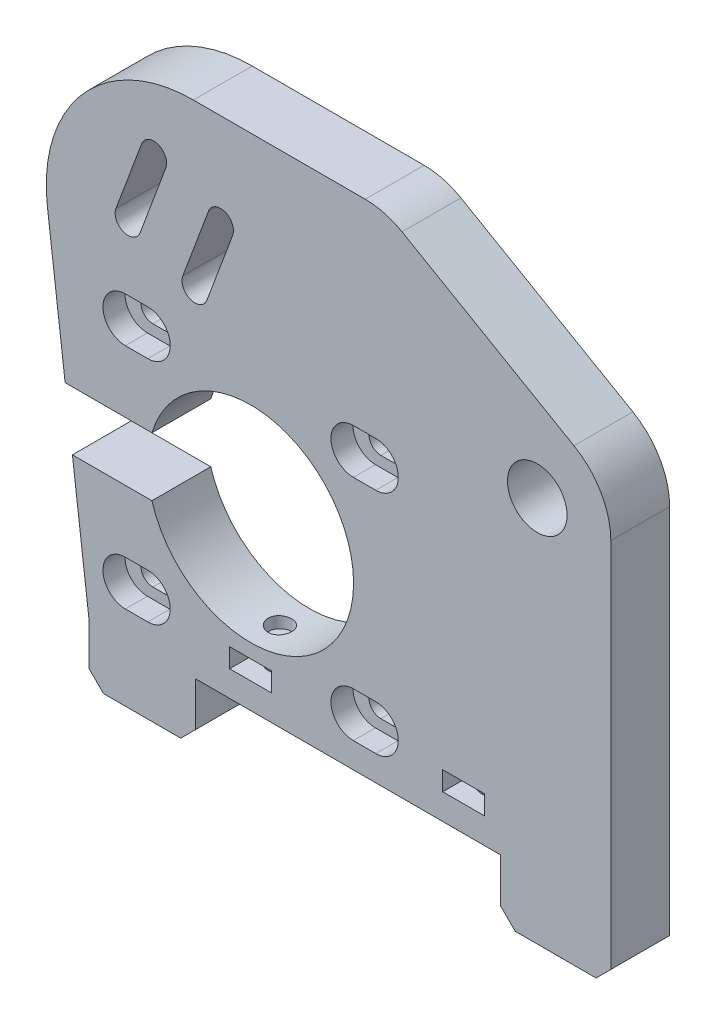
SolidWorks part; units mm, degrees
ref_plane "前视基准面" through (0, 0, 0) normal (0, 0, 1) x (1, 0, 0)
ref_plane "上视基准面" through (0, 0, 0) normal (0, 1, 0) x (1, 0, 0)
ref_plane "右视基准面" through (0, 0, 0) normal (1, 0, 0) x (0, 0, -1)
sketch "草图1" plane through (0, 0, 0) normal (0, 0, 1) x (1, 0, 0)
  line B0 (-25.2132, 4) -> (-29.6202, 39.6595)
  line B1 (-13.4164, 4) -> (-25.2132, 4)
  line B2 (-24.2245, -4) -> (-13.4164, -4)
  line B3 (-22, -22) -> (-24.2245, -4)
  line B4 (-7.5, -30) -> (-22, -30)
  line B5 (-7.5, -30) -> (-7.5, -22)
  line B6 (33.9711, -22) -> (-7.5, -22)
  line B7 (-14.7, 13.9) -> (-16.3, 13.9)
  line B8 (-16.3, 17.1) -> (-14.7, 17.1)
  line B9 (16.3, 13.9) -> (14.7, 13.9)
  line B10 (14.7, 17.1) -> (16.3, 17.1)
  line B11 (31.9711, -15.5) -> (25.9711, -15.5)
  line B12 (31.9711, -18.5) -> (31.9711, -15.5)
  line B13 (25.9711, -18.5) -> (31.9711, -18.5)
  line B14 (25.9711, -15.5) -> (25.9711, -18.5)
  line B15 (16.3, -17.1) -> (14.7, -17.1)
  line B16 (14.7, -13.9) -> (16.3, -13.9)
  line B17 (3, -15.5) -> (-3, -15.5)
  line B18 (3, -18.5) -> (3, -15.5)
  line B19 (-3, -18.5) -> (3, -18.5)
  line B20 (-3, -15.5) -> (-3, -18.5)
  line B21 (-14.7, -17.1) -> (-16.3, -17.1)
  line B22 (-16.3, -13.9) -> (-14.7, -13.9)
  line B23 (33.9711, -30) -> (33.9711, -22)
  line B24 (48.9711, -30) -> (33.9711, -30)
  line B25 (48.9711, 22.5) -> (48.9711, -30)
  line B26 (-22, -30) -> (-22, -22)
  line B27 (30.5711, -7) -> (27.3711, -7) construction
  line B28 (-17.025, -12.45) -> (-13.975, -12.45) construction
  line B29 (13.975, -12.45) -> (17.025, -12.45) construction
  line B30 (17.025, -18.55) -> (13.975, -18.55) construction
  line B31 (17.025, 12.45) -> (13.975, 12.45) construction
  line B32 (13.975, 18.55) -> (17.025, 18.55) construction
  line B33 (-13.975, 12.45) -> (-17.025, 12.45) construction
  line B34 (-17.025, 18.55) -> (-13.975, 18.55) construction
  line B35 (-13.975, -18.55) -> (-17.025, -18.55) construction
  line B36 (-1.6, -22) -> (-1.6, -18.5) construction
  line B37 (1.6, -18.5) -> (1.6, -22) construction
  line B38 (-1.6, -15.5) -> (-1.6, -13.9083) construction
  line B39 (30.5711, -18.5) -> (30.5711, -22) construction
  line B40 (27.3711, -15.5) -> (27.3711, -7) construction
  line B41 (30.5711, -7) -> (30.5711, -15.5) construction
  line B42 (43.9711, 31.1603) -> (-7.9904, 61.1603)
  line B43 (-28.356, 45.886) -> (-21.6506, 57.5)
  circle B44 centre (-12.9904, 52.5) radius 6.5
  circle B45 centre (38.9711, 22.5) radius 4.05
  circle B46 centre (-12.9904, 52.5) radius 4.7
  arc B47 (-13.4164, -4) -> (-13.4164, 4) centre (0, 0) ccw
  arc B48 (-14.7, 13.9) -> (-14.7, 17.1) centre (-14.7, 15.5) ccw
  arc B49 (-16.3, 17.1) -> (-16.3, 13.9) centre (-16.3, 15.5) ccw
  arc B50 (16.3, 13.9) -> (16.3, 17.1) centre (16.3, 15.5) ccw
  arc B51 (14.7, 17.1) -> (14.7, 13.9) centre (14.7, 15.5) ccw
  arc B52 (16.3, -17.1) -> (16.3, -13.9) centre (16.3, -15.5) ccw
  arc B53 (14.7, -13.9) -> (14.7, -17.1) centre (14.7, -15.5) ccw
  arc B54 (-14.7, -17.1) -> (-14.7, -13.9) centre (-14.7, -15.5) ccw
  arc B55 (-16.3, -13.9) -> (-16.3, -17.1) centre (-16.3, -15.5) ccw
  arc B56 (17.025, -18.55) -> (17.025, -12.45) centre (17.025, -15.5) ccw construction
  arc B57 (17.025, 12.45) -> (17.025, 18.55) centre (17.025, 15.5) ccw construction
  arc B58 (13.975, 18.55) -> (13.975, 12.45) centre (13.975, 15.5) ccw construction
  arc B59 (13.975, -12.45) -> (13.975, -18.55) centre (13.975, -15.5) ccw construction
  arc B60 (-17.025, 18.55) -> (-17.025, 12.45) centre (-17.025, 15.5) ccw construction
  arc B61 (-17.025, -12.45) -> (-17.025, -18.55) centre (-17.025, -15.5) ccw construction
  arc B62 (-13.975, -18.55) -> (-13.975, -12.45) centre (-13.975, -15.5) ccw construction
  arc B63 (-13.975, 12.45) -> (-13.975, 18.55) centre (-13.975, 15.5) ccw construction
  arc B64 (-7.9904, 61.1603) -> (-21.6506, 57.5) centre (-12.9904, 52.5) ccw
  arc B65 (48.9711, 22.5) -> (43.9711, 31.1603) centre (38.9711, 22.5) ccw
  arc B66 (-28.356, 45.886) -> (-29.6202, 39.6595) centre (-19.6957, 40.886) ccw
sketch_block_instance "mainStructure3-1_0-1"
sketch_block "mainStructure3-1_0"
sketch "草图3" plane through (0, 0, 0) normal (0, 0, 1) x (1, 0, 0)
  line L0 (-3.05, -15.5) -> (-3.05, -18.5)
  line L1 (3.05, -15.5) -> (3.05, -18.5)
  line L2 (-3, -15.5) -> (-3, -18.5) construction
  line L3 (-13.4164, 4) -> (-25.2132, 4) construction
  line L4 (-24.2245, -4) -> (-13.4164, -4) construction
  line L5 (-22, -22) -> (-24.2245, -4) construction
  line L6 (-22, -30) -> (-22, -22) construction
  line L7 (-7.5, -30) -> (-22, -30) construction
  line L8 (33.9711, -22) -> (-7.5, -22) construction
  line L9 (-7.5, -30) -> (-7.5, -22) construction
  line L10 (48.9711, -30) -> (33.9711, -30) construction
  line L11 (33.9711, -30) -> (33.9711, -22) construction
  line L12 (48.9711, 22.5) -> (48.9711, -30) construction
  line L13 (-16.3, 17.1) -> (-14.7, 17.1) construction
  line L14 (-14.7, 13.9) -> (-16.3, 13.9) construction
  line L15 (14.7, 17.1) -> (16.3, 17.1) construction
  line L16 (16.3, 13.9) -> (14.7, 13.9) construction
  line L17 (14.7, -13.9) -> (16.3, -13.9) construction
  line L18 (16.3, -17.1) -> (14.7, -17.1) construction
  line L19 (-16.3, -13.9) -> (-14.7, -13.9) construction
  line L20 (-14.7, -17.1) -> (-16.3, -17.1) construction
  line L21 (43.9711, 31.1603) -> (-7.9904, 61.1603) construction
  line L22 (43.9711, 31.1603) -> (20.5885, 44.6603)
  line L23 (-25.2132, 4) -> (-29.6202, 39.6595) construction
  line L24 (-13.4164, 4) -> (-25.2132, 4)
  line L25 (-24.2245, -4) -> (-13.4164, -4)
  line L26 (-22, -22) -> (-24.2245, -4)
  line L27 (-22, -30) -> (-22, -22)
  line L28 (-7.5, -30) -> (-22, -30)
  line L29 (33.9711, -22) -> (-7.5, -22)
  line L30 (-7.5, -30) -> (-7.5, -22)
  line L31 (48.9711, -30) -> (33.9711, -30)
  line L32 (33.9711, -30) -> (33.9711, -22)
  line L33 (48.9711, 22.5) -> (48.9711, -30)
  line L34 (-16.3, 17.1) -> (-14.7, 17.1)
  line L35 (-14.7, 13.9) -> (-16.3, 13.9)
  line L36 (14.7, 17.1) -> (16.3, 17.1)
  line L37 (16.3, 13.9) -> (14.7, 13.9)
  line L38 (14.7, -13.9) -> (16.3, -13.9)
  line L39 (16.3, -17.1) -> (14.7, -17.1)
  line L40 (-16.3, -13.9) -> (-14.7, -13.9)
  line L41 (-14.7, -17.1) -> (-16.3, -17.1)
  line L42 (3, -15.5) -> (-3, -15.5) construction
  line L44 (-3, -18.5) -> (3, -18.5) construction
  line L46 (31.9711, -15.5) -> (25.9711, -15.5) construction
  line L49 (25.9711, -18.5) -> (31.9711, -18.5) construction
  line L50 (3.05, -15.5) -> (-3.05, -15.5)
  line L51 (25.9211, -15.5) -> (25.9211, -18.5)
  line L52 (-3.05, -18.5) -> (3.05, -18.5)
  line L53 (32.0211, -15.5) -> (32.0211, -18.5)
  line L54 (32.0211, -15.5) -> (25.9211, -15.5)
  line L55 (25.9711, -15.5) -> (25.9711, -18.5) construction
  line L57 (25.9211, -18.5) -> (32.0211, -18.5)
  line L58 (-25.2132, 4) -> (-27.6289, 23.547)
  line L59 (15.5885, 46) -> (-7.7799, 46)
  arc A2 (-13.4164, -4) -> (-13.4164, 4) centre (0, 0) ccw construction
  circle A4 centre (38.9711, 22.5) radius 4.05 construction
  arc A6 (-14.7, 13.9) -> (-14.7, 17.1) centre (-14.7, 15.5) ccw construction
  arc A7 (-16.3, 17.1) -> (-16.3, 13.9) centre (-16.3, 15.5) ccw construction
  arc A8 (14.7, 17.1) -> (14.7, 13.9) centre (14.7, 15.5) ccw construction
  arc A9 (16.3, 13.9) -> (16.3, 17.1) centre (16.3, 15.5) ccw construction
  arc A10 (16.3, -17.1) -> (16.3, -13.9) centre (16.3, -15.5) ccw construction
  arc A11 (14.7, -13.9) -> (14.7, -17.1) centre (14.7, -15.5) ccw construction
  arc A12 (-16.3, -13.9) -> (-16.3, -17.1) centre (-16.3, -15.5) ccw construction
  arc A13 (-14.7, -17.1) -> (-14.7, -13.9) centre (-14.7, -15.5) ccw construction
  arc A14 (48.9711, 22.5) -> (43.9711, 31.1603) centre (38.9711, 22.5) ccw construction
  arc A15 (48.9711, 22.5) -> (43.9711, 31.1603) centre (38.9711, 22.5) ccw
  arc A16 (-13.4164, -4) -> (-13.4164, 4) centre (0, 0) ccw
  circle A17 centre (-12.9904, 52.5) radius 6.5 construction
  circle A18 centre (38.9711, 22.5) radius 4.05
  arc A19 (20.5885, 44.6603) -> (15.5885, 46) centre (15.5885, 36) ccw
  arc A20 (-14.7, 13.9) -> (-14.7, 17.1) centre (-14.7, 15.5) ccw
  arc A21 (-16.3, 17.1) -> (-16.3, 13.9) centre (-16.3, 15.5) ccw
  arc A22 (14.7, 17.1) -> (14.7, 13.9) centre (14.7, 15.5) ccw
  arc A23 (16.3, 13.9) -> (16.3, 17.1) centre (16.3, 15.5) ccw
  arc A24 (16.3, -17.1) -> (16.3, -13.9) centre (16.3, -15.5) ccw
  arc A25 (14.7, -13.9) -> (14.7, -17.1) centre (14.7, -15.5) ccw
  arc A26 (-16.3, -13.9) -> (-16.3, -17.1) centre (-16.3, -15.5) ccw
  arc A27 (-14.7, -17.1) -> (-14.7, -13.9) centre (-14.7, -15.5) ccw
  arc A28 (-27.6289, 23.547) -> (-7.7799, 46) centre (-7.7799, 26) cw
  dimension "D1" = 10
  dimension "D2" = 20
  dimension "D3" = 6.1
  dimension "D4" = 0.05
  dimension "D5" = 6.1
  dimension "D6" = 0.05
extrude "凸台-拉伸1" add sketch "草图3" along normal blind 8
sketch "草图5" plane through (0, 0, 8) normal (0, 0, 1) x (1, 0, 0)
  line L0 (-17.025, 18.55) -> (-13.975, 18.55) construction
  line L1 (-13.975, 12.45) -> (-17.025, 12.45) construction
  line L2 (13.975, 18.55) -> (17.025, 18.55) construction
  line L3 (17.025, 12.45) -> (13.975, 12.45) construction
  line L4 (13.975, -12.45) -> (17.025, -12.45) construction
  line L5 (17.025, -18.55) -> (13.975, -18.55) construction
  line L6 (-17.025, -12.45) -> (-13.975, -12.45) construction
  line L7 (-13.975, -18.55) -> (-17.025, -18.55) construction
  line L8 (-17.025, 18.55) -> (-13.975, 18.55)
  line L9 (-13.975, 12.45) -> (-17.025, 12.45)
  line L10 (13.975, 18.55) -> (17.025, 18.55)
  line L11 (17.025, 12.45) -> (13.975, 12.45)
  line L12 (13.975, -12.45) -> (17.025, -12.45)
  line L13 (17.025, -18.55) -> (13.975, -18.55)
  line L14 (-17.025, -12.45) -> (-13.975, -12.45)
  line L15 (-13.975, -18.55) -> (-17.025, -18.55)
  arc A0 (-13.975, 12.45) -> (-13.975, 18.55) centre (-13.975, 15.5) ccw construction
  arc A1 (-17.025, 18.55) -> (-17.025, 12.45) centre (-17.025, 15.5) ccw construction
  arc A2 (17.025, 12.45) -> (17.025, 18.55) centre (17.025, 15.5) ccw construction
  arc A3 (13.975, 18.55) -> (13.975, 12.45) centre (13.975, 15.5) ccw construction
  arc A4 (17.025, -18.55) -> (17.025, -12.45) centre (17.025, -15.5) ccw construction
  arc A5 (13.975, -12.45) -> (13.975, -18.55) centre (13.975, -15.5) ccw construction
  arc A6 (-13.975, -18.55) -> (-13.975, -12.45) centre (-13.975, -15.5) ccw construction
  arc A7 (-17.025, -12.45) -> (-17.025, -18.55) centre (-17.025, -15.5) ccw construction
  arc A8 (-13.975, 12.45) -> (-13.975, 18.55) centre (-13.975, 15.5) ccw
  arc A9 (-17.025, 18.55) -> (-17.025, 12.45) centre (-17.025, 15.5) ccw
  arc A10 (17.025, 12.45) -> (17.025, 18.55) centre (17.025, 15.5) ccw
  arc A11 (13.975, 18.55) -> (13.975, 12.45) centre (13.975, 15.5) ccw
  arc A12 (17.025, -18.55) -> (17.025, -12.45) centre (17.025, -15.5) ccw
  arc A13 (13.975, -12.45) -> (13.975, -18.55) centre (13.975, -15.5) ccw
  arc A14 (-13.975, -18.55) -> (-13.975, -12.45) centre (-13.975, -15.5) ccw
  arc A15 (-17.025, -12.45) -> (-17.025, -18.55) centre (-17.025, -15.5) ccw
extrude "切除-拉伸2" cut sketch "草图5" against normal blind 3
sketch "草图6" plane through (0, -22, 0) normal (0, -1, 0) x (1, 0, 0)
  line L0 (-7.5, 8) -> (-7.5, 0) construction
  line L1 (33.9711, 8) -> (33.9711, 0) construction
  line L2 (-7.5, 8) -> (33.9711, 8) construction
  circle A0 centre (0, 4) radius 1.6
  circle A1 centre (28.9711, 4) radius 1.6
  dimension "D4" = 3.2
  dimension "D1" = 7.5
  dimension "D2" = 5
  dimension "D3" = 4
extrude "切除-拉伸3" cut sketch "草图6" against normal up to vertex (15 mm away)
sketch "草图7" plane through (0, 0, 8) normal (0, 0, 1) x (1, 0, 0)
  line B0 (-9.216, 24.5748) -> (-5.7204, 33.944)
  line B1 (-5.9368, 23.3514) -> (-2.4412, 32.7205)
  line B2 (-18.3041, 27.9656) -> (-14.8085, 37.3347)
  line B3 (-15.0249, 26.7421) -> (-11.5293, 36.1112)
  circle B4 centre (38.9711, 22.5) radius 4.05
  arc B5 (-9.216, 24.5748) -> (-5.9368, 23.3514) centre (-7.5764, 23.9631) ccw
  arc B6 (-18.3041, 27.9656) -> (-15.0249, 26.7421) centre (-16.6645, 27.3538) ccw
  arc B7 (-2.4412, 32.7205) -> (-5.7204, 33.944) centre (-4.0808, 33.3322) ccw
  arc B8 (-11.5293, 36.1112) -> (-14.8085, 37.3347) centre (-13.1689, 36.723) ccw
sketch_block_instance "块1-1"
sketch_block "块1"
extrude "切除-拉伸4" cut sketch "草图7" against normal through all
chamfer "倒角1" distance 2 angle 45 4 edges at (48.9711, -30, 4) (33.9711, -30, 4) (-7.5, -30, 4) (-22, -30, 4)
sketch "草图8" plane through (0, 0, 8) normal (0, 0, 1) x (1, 0, 0)
  line L0 (-3, -18.5) -> (3, -18.5) construction
  line L1 (25.9211, -15.5) -> (25.9211, -18.5)
  line L2 (-2.85, -18.5) -> (-2.85, -15.9)
  line L3 (-2.85, -15.9) -> (2.85, -15.9)
  line L4 (2.85, -18.5) -> (2.85, -15.9)
  line L5 (3, -18.5) -> (3, -15.5) construction
  line L6 (25.9711, -18.5) -> (31.9711, -18.5) construction
  line L7 (-2.85, -18.5) -> (-3.05, -18.5)
  line L8 (26.1211, -18.5) -> (26.1211, -15.9)
  line L9 (26.1211, -15.9) -> (31.8211, -15.9)
  line L10 (31.8211, -18.5) -> (31.8211, -15.9)
  line L11 (31.9711, -18.5) -> (31.9711, -15.5) construction
  line L12 (26.1211, -18.5) -> (25.9211, -18.5)
  line L13 (25.9211, -15.5) -> (25.9211, -18.5) construction
  line L14 (25.9211, -15.5) -> (32.0211, -15.5)
  line L15 (32.0211, -15.5) -> (32.0211, -18.5)
  line L16 (32.0211, -18.5) -> (31.8211, -18.5)
  line L17 (-3.05, -15.5) -> (-3.05, -18.5) construction
  line L18 (-3.05, -18.5) -> (-3.05, -15.5)
  line L19 (-3.05, -15.5) -> (3.05, -15.5)
  line L20 (3.05, -15.5) -> (3.05, -18.5)
  line L21 (3.05, -18.5) -> (2.85, -18.5)
  dimension "D1" = 2.6
  dimension "D2" = 5.7
  dimension "D3" = 0.15
  dimension "D4" = 2.6
  dimension "D5" = 5.7
  dimension "D6" = 0.15
extrude "凸台-拉伸2" add sketch "草图8" against normal up to vertex (8 mm away)
